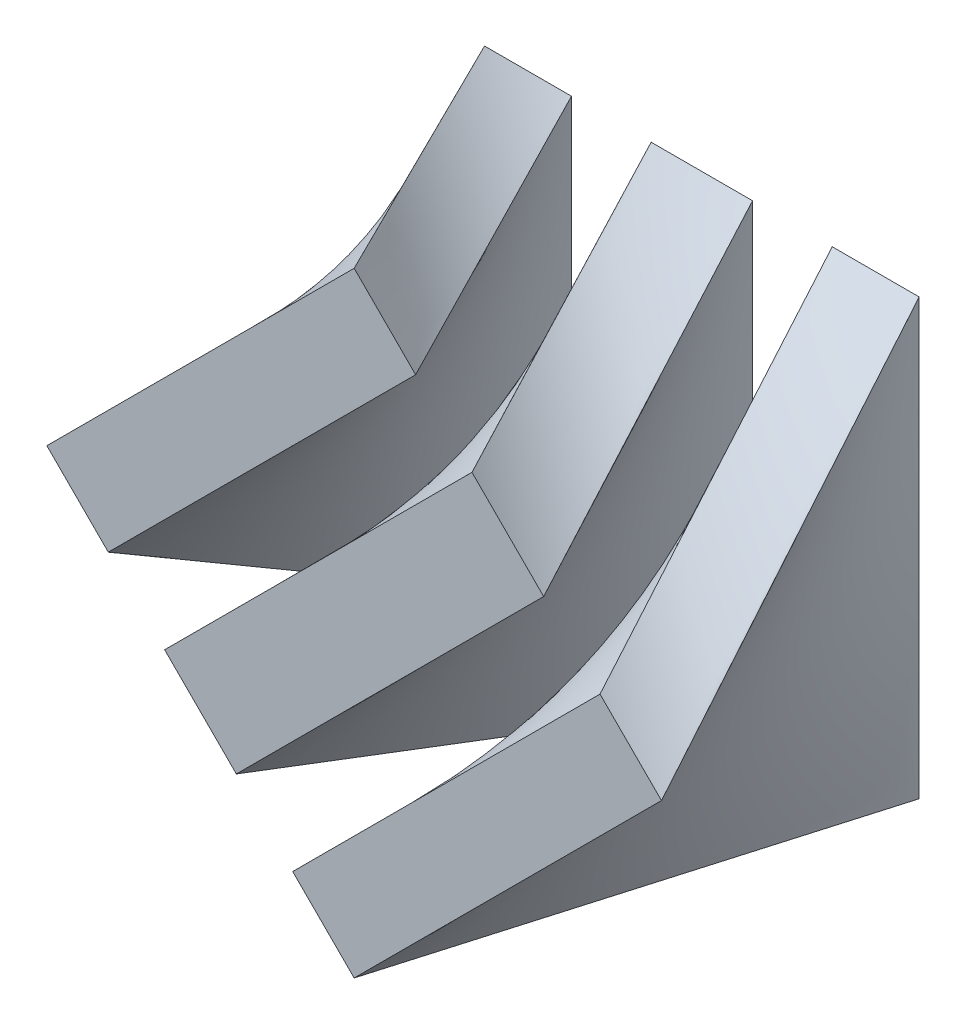
SolidWorks part; units mm, degrees
ref_plane "Front Plane" through (0, 0, 0) normal (0, 0, 1) x (1, 0, 0)
ref_plane "Top Plane" through (0, 0, 0) normal (0, 1, 0) x (1, 0, 0)
ref_plane "Right Plane" through (0, 0, 0) normal (1, 0, 0) x (0, 0, -1)
sketch "Sketch1" plane through (0, 0, 0) normal (0, 0, 1) x (1, 0, 0)
  line L0 (0, 0) -> (15, 0) construction
  line L1 (0, -7.5) -> (3, -7.5)
  line L2 (0, -7.5) -> (0, 7.5)
  line L3 (0, 7.5) -> (3, 7.5)
  line L4 (3, -7.5) -> (3, 7.5)
  line L5 (7.5, -7.5) -> (7.5, 7.5) construction
  point P9 (7.5, 0)
  point P10 (7.5, 0)
  point P11 (0, 0)
  dimension "D1" = 15
  dimension "D2" = 3
  dimension "D3" = 15
  dimension "D4" = 15
sketch "Sketch3" plane through (0, 0, 0) normal (0, 0, 1) x (1, 0, 0)
  line L0 (0, -7.5) -> (3, -7.5) construction
  line L1 (5.75, -7.5) -> (9.25, -7.5)
  line L2 (5.75, -7.5) -> (5.75, 7.5)
  line L3 (5.75, 7.5) -> (9.25, 7.5)
  line L4 (9.25, -7.5) -> (9.25, 7.5)
  line L6 (0, 7.5) -> (3, 7.5) construction
  line L7 (0, 0) -> (15, 0) construction
  line L8 (7.5, -7.5) -> (7.5, 7.5) construction
  point P6 (7.5, 0)
  point P7 (7.5, 0)
  dimension "D1" = 15
  dimension "D2" = 3.5
sketch "Sketch4" plane through (0, 0, 0) normal (0, 0, 1) x (1, 0, 0)
  line L0 (0, -7.5) -> (3, -7.5) construction
  line L1 (12, -7.5) -> (15, -7.5)
  line L2 (12, -7.5) -> (12, 7.5)
  line L3 (12, 7.5) -> (15, 7.5)
  line L4 (15, -7.5) -> (15, 7.5)
  line L5 (0, 7.5) -> (3, 7.5) construction
  line L7 (0, 0) -> (15, 0) construction
  line L8 (7.5, -7.5) -> (7.5, 7.5) construction
  point P13 (0, 0)
  point P14 (7.5, 0)
  point P15 (7.5, 0)
  dimension "D1" = 3
  dimension "D2" = 15
ref_plane "Plane1" through (0, 0, 12) normal (0, 0, 1) x (1, 0, 0)
sketch "Sketch2" plane through (0, 0, 12) normal (0, 0, 1) x (1, 0, 0)
  line L0 (-3.1066, 0) -> (7.5, 10.6066)
  line L1 (7.5, 10.6066) -> (9.6213, 8.4853)
  line L2 (9.6213, 8.4853) -> (-0.9853, -2.1213)
  line L3 (-0.9853, -2.1213) -> (-3.1066, 0)
  line L4 (2.1967, 5.3033) -> (12.8033, -5.3033) construction
  line L5 (0, 0) -> (15, 0) construction
  point P7 (7.5, 0)
  point P11 (7.5, 0)
  point P12 (-0.3138, -4.0117)
  dimension "D1" = 3
  dimension "D2" = 15
  dimension "D3" = 15
  dimension "D4" = 45
sketch "Sketch5" plane through (0, 0, 12) normal (0, 0, 1) x (1, 0, 0)
  line L0 (0.9593, -4.0659) -> (11.5659, 6.5407)
  line L1 (11.5659, 6.5407) -> (14.0407, 4.0659)
  line L2 (14.0407, 4.0659) -> (3.4341, -6.5407)
  line L3 (3.4341, -6.5407) -> (0.9593, -4.0659)
  line L7 (2.1967, 5.3033) -> (12.8033, -5.3033) construction
  line L8 (0, 0) -> (15, 0) construction
  line L9 (2.1967, -5.3033) -> (12.8033, 5.3033) construction
  point P2 (7.5, 0)
  point P10 (7.5, 0)
  point P15 (7.5, 0)
  dimension "D1" = 15
  dimension "D2" = 45
  dimension "D3" = 3.5
  dimension "D4" = 15
sketch "Sketch6" plane through (0, 0, 12) normal (0, 0, 1) x (1, 0, 0)
  line L0 (5.3787, -8.4853) -> (15.9853, 2.1213)
  line L1 (15.9853, 2.1213) -> (18.1066, 0)
  line L2 (18.1066, 0) -> (7.5, -10.6066)
  line L3 (7.5, -10.6066) -> (5.3787, -8.4853)
  line L5 (12.8033, -5.3033) -> (2.1967, 5.3033) construction
  line L7 (2.1967, -5.3033) -> (12.8033, 5.3033) construction
  line L8 (0, 0) -> (15, 0) construction
  point P2 (16.098, 2.901)
  point P5 (2.7167, 5.7767)
  point P10 (7.5, 0)
  point P11 (7.5, 0)
  point P12 (7.5, 0)
  point P15 (0, 0)
  point P16 (12.8033, 5.3033)
  dimension "D1" = 15
  dimension "D2" = 15
  dimension "D3" = 45
  dimension "D4" = 4.5
loft "Loft5" add profiles "Sketch2", "Sketch1"
loft "Loft6" add profiles "Sketch5", "Sketch3"
loft "Loft7" add profiles "Sketch6", "Sketch4"
